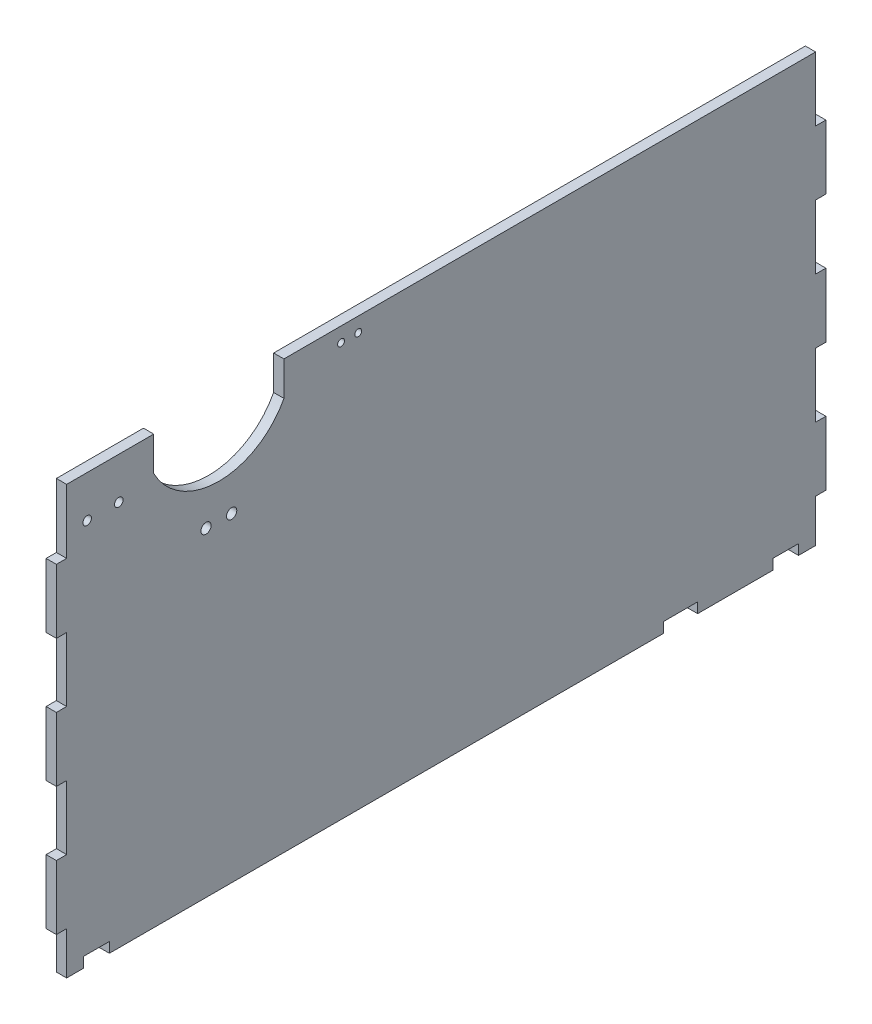
SolidWorks part; units mm, degrees
ref_plane "Front" through (0, 0, 0) normal (0, 0, 1) x (1, 0, 0)
ref_plane "Top" through (0, 0, 0) normal (0, 1, 0) x (1, 0, 0)
ref_plane "Right" through (0, 0, 0) normal (1, 0, 0) x (0, 0, -1)
sketch "Sketch1" plane through (0, 0, 0) normal (1, 0, 0) x (0, 0, -1)
  line L1 (0, 0) -> (-450, 0)
  line L2 (0, 0) -> (0, 250)
  line L3 (0, 250) -> (-450, 250)
  line L4 (-450, 0) -> (-450, 250)
  dimension "D1" = 450
  dimension "D2" = 250
extrude "Boss-Extrude1" add sketch "Sketch1" along normal blind 6
sketch "Sketch2" plane through (6, 0, 0) normal (1, 0, 0) x (0, 0, -1)
  line L0 (-450, 250) -> (-450, 0) construction
  line L1 (-450, 250) -> (-444, 250)
  line L2 (-450, 250) -> (-450, 212.5)
  line L3 (-450, 212.5) -> (-444, 212.5)
  line L4 (-444, 250) -> (-444, 212.5)
  line L5 (0, 250) -> (-450, 250) construction
  dimension "D1" = 6
  dimension "D2" = 37.5
extrude "Cut-Extrude1" cut sketch "Sketch2" against normal through all
pattern_linear "LPattern1" count 4 spacing 75 along (0, -1, 0) count 2 spacing 444 along (0, 0, -1) of "Cut-Extrude1"
sketch "Sketch3" plane through (6, 0, 0) normal (1, 0, 0) x (0, 0, -1)
  line L0 (-444, 0) -> (-6, 0) construction
  line L1 (-434, 0) -> (-419, 0)
  line L2 (-434, 0) -> (-434, 6)
  line L3 (-434, 6) -> (-419, 6)
  line L4 (-419, 0) -> (-419, 6)
  line L6 (-444, 62.5) -> (-444, 100) construction
  dimension "D1" = 10
  dimension "D2" = 15
  dimension "D3" = 6
extrude "Cut-Extrude2" cut sketch "Sketch3" against normal through all
pattern_linear "LPattern2" count 2 spacing 403 along (0, 0, -1) of "Cut-Extrude2"
sketch "Sketch4" plane through (6, 0, 0) normal (1, 0, 0) x (0, 0, -1)
  line L0 (-393.0657, 230) -> (-316.9343, 230) construction
  line L1 (-355, 250) -> (-355, 207) construction
  line L2 (-450, 212.5) -> (-450, 175) construction
  line L3 (-393.0657, 230) -> (-393.0657, 250)
  line L4 (-6, 250) -> (-444, 250) construction
  line L5 (-393.0657, 250) -> (-316.9343, 250)
  line L6 (-316.9343, 250) -> (-316.9343, 230)
  arc A0 (-393.0657, 230) -> (-316.9343, 230) centre (-355, 250) ccw
  circle A1 centre (-362.5, 187) radius 3
  circle A3 centre (-347.5, 187) radius 3
  dimension "D4" = 63
  dimension "D1" = 43
  dimension "D6" = 6
  dimension "D2" = 20
  dimension "D3" = 95
  dimension "D5" = 7.5
extrude "Cut-Extrude3" cut sketch "Sketch4" against normal blind 10
sketch "Sketch5" plane through (6, 0, 0) normal (1, 0, 0) x (0, 0, -1)
  line L0 (-419, 0) -> (-31, 0) construction
  line L1 (-75, 0) -> (-95, 0)
  line L2 (-75, 0) -> (-75, 6)
  line L3 (-75, 6) -> (-95, 6)
  line L4 (-95, 0) -> (-95, 6)
  line L5 (-16, 6) -> (-31, 6) construction
  line L6 (0, 25) -> (0, 62.5) construction
  dimension "D1" = 20
  dimension "D2" = 75
extrude "Cut-Extrude4" cut sketch "Sketch5" against normal through all
sketch "Sketch6" plane through (0, 0, 0) normal (-1, 0, 0) x (0, 0, 1)
  line L0 (444, 212.5) -> (444, 250) construction
  line L1 (6, 250) -> (316.9343, 250) construction
  line L2 (393.0657, 250) -> (444, 250) construction
  circle A0 centre (432, 225.7) radius 2.5
  circle A1 centre (413.5, 225.7) radius 2.5
  circle A2 centre (283.51, 241.5) radius 2
  circle A3 centre (273.51, 241.5) radius 2
  dimension "D1" = 12
  dimension "D5" = 4
  dimension "D6" = 5
  dimension "D2" = 18.5
  dimension "D3" = 10
  dimension "D4" = 160.49
  dimension "D7" = 8.5
  dimension "D8" = 24.3
extrude "Cut-Extrude5" cut sketch "Sketch6" against normal through all
